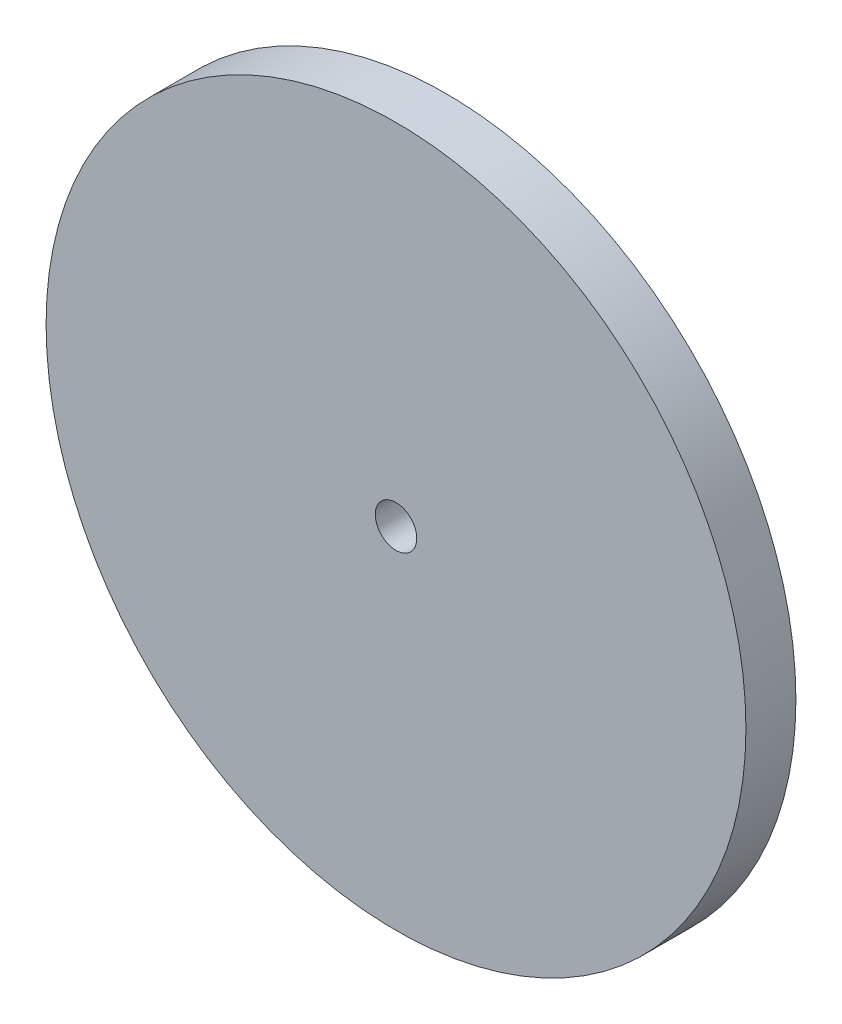
SolidWorks part; units mm, degrees
ref_plane "Alzado" through (0, 0, 0) normal (0, 0, 1) x (1, 0, 0)
ref_plane "Planta" through (0, 0, 0) normal (0, 1, 0) x (1, 0, 0)
ref_plane "Vista lateral" through (0, 0, 0) normal (1, 0, 0) x (0, 0, -1)
sketch "Croquis1" plane through (0, 0, 0) normal (0, 0, 1) x (1, 0, 0)
  circle A0 centre (0, 0) radius 35
  dimension "D1" = 70
extrude "Saliente-Extruir1" add sketch "Croquis1" along normal blind 5
sketch "Croquis2" plane through (0, 0, 0) normal (0, 0, -1) x (-1, 0, 0)
  circle A0 centre (0, 0) radius 2.075
  dimension "D1" = 4.15
extrude "Cortar-Extruir1" cut sketch "Croquis2" against normal through all
